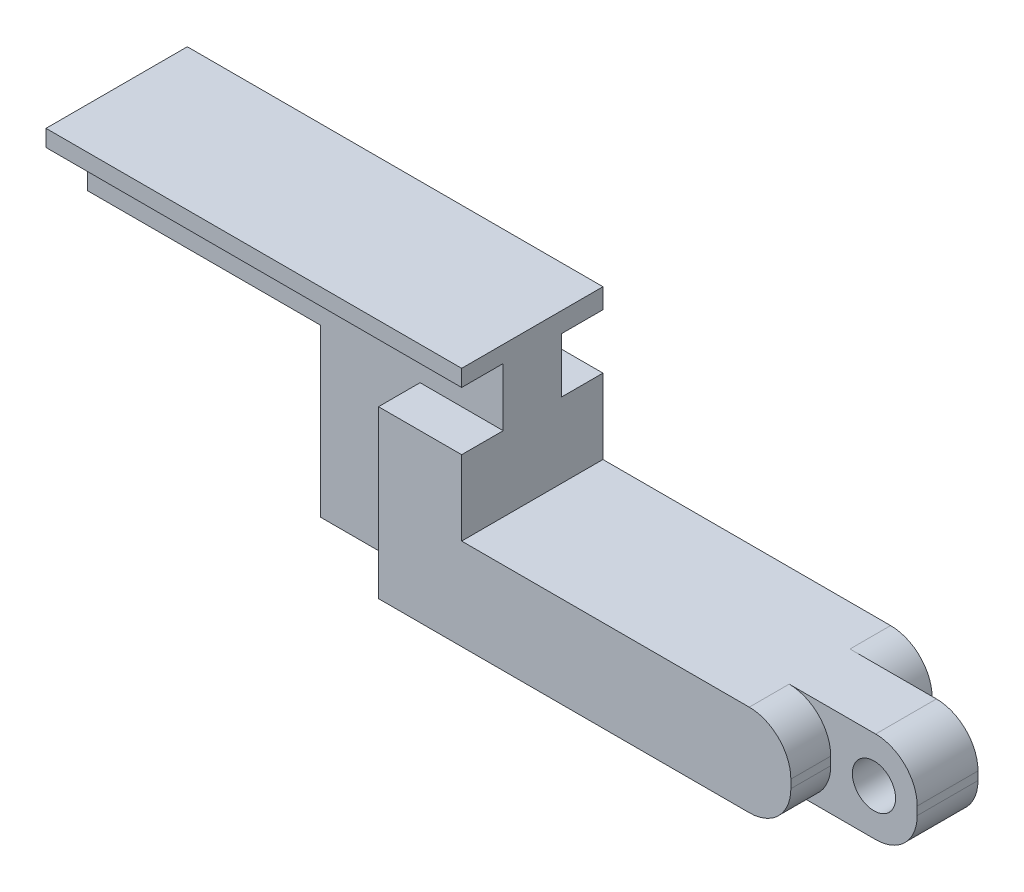
SolidWorks part; units mm, degrees
ref_plane "Front Plane" through (0, 0, 0) normal (0, 0, 1) x (1, 0, 0)
ref_plane "Top Plane" through (0, 0, 0) normal (0, 1, 0) x (1, 0, 0)
ref_plane "Right Plane" through (0, 0, 0) normal (1, 0, 0) x (0, 0, -1)
sketch "Sketch1" plane through (0, 0, 0) normal (1, 0, 0) x (0, 0, -1)
  line L0 (0, 0) -> (0, -36.83)
  line L1 (0, -36.83) -> (21.59, -36.83)
  line L2 (21.59, -36.83) -> (21.59, 0)
  line L3 (21.59, 0) -> (0, 0)
  dimension "D1" = 21.59
  dimension "D2" = 36.83
extrude "Boss-Extrude1" add sketch "Sketch1" along normal blind 127
sketch "Sketch2" plane through (0, 0, 0) normal (0, 0, 1) x (1, 0, 0)
  line L0 (0, -36.83) -> (0, -11.43)
  line L1 (0, 0) -> (0, -36.83) construction
  line L2 (0, -11.43) -> (50.8, -11.43)
  line L3 (50.8, -11.43) -> (50.8, -36.83)
  line L4 (127, -36.83) -> (0, -36.83) construction
  line L5 (50.8, -36.83) -> (0, -36.83)
  dimension "D1" = 50.8
  dimension "D2" = 25.4
extrude "Cut-Extrude1" cut sketch "Sketch2" against normal blind 25.4
sketch "Sketch3" plane through (0, 0, 0) normal (0, 0, 1) x (1, 0, 0)
  line L0 (127, 0) -> (63.5, 0)
  line L1 (127, 0) -> (0, 0) construction
  line L2 (63.5, 0) -> (63.5, -22.86)
  line L3 (63.5, -22.86) -> (127, -22.86)
  line L4 (127, 0) -> (127, -36.83) construction
  line L5 (127, -22.86) -> (127, 0)
  dimension "D1" = 63.5
  dimension "D2" = 22.86
extrude "Cut-Extrude2" cut sketch "Sketch3" against normal blind 22.86
sketch "Sketch4" plane through (0, 0, 0) normal (-1, 0, 0) x (0, 0, 1)
  line L0 (-21.59, -11.43) -> (-15.24, -11.43)
  line L1 (-21.59, -11.43) -> (0, -11.43) construction
  line L2 (-15.24, -11.43) -> (-15.24, -3.048)
  line L3 (-15.24, -3.048) -> (-21.59, -3.048)
  line L4 (-21.59, -11.43) -> (-21.59, 0) construction
  line L5 (-21.59, -3.048) -> (-21.59, -11.43)
  dimension "D1" = 8.382
  dimension "D2" = 6.35
extrude "Cut-Extrude3" cut sketch "Sketch4" against normal blind 69.85
sketch "Sketch5" plane through (0, 0, 0) normal (-1, 0, 0) x (0, 0, 1)
  line L0 (0, -11.43) -> (-6.35, -11.43)
  line L1 (-15.24, -11.43) -> (0, -11.43) construction
  line L2 (-6.35, -11.43) -> (-6.35, -2.54)
  line L3 (-6.35, -2.54) -> (0, -2.54)
  line L4 (0, 0) -> (0, -11.43) construction
  line L5 (0, -2.54) -> (0, -11.43)
  dimension "D1" = 8.89
  dimension "D2" = 6.35
extrude "Cut-Extrude4" cut sketch "Sketch5" against normal blind 69.85
sketch "Sketch6" plane through (127, 0, 0) normal (1, 0, 0) x (0, 0, -1)
  line L0 (0, -36.83) -> (0, -22.86)
  line L1 (0, -22.86) -> (6.096, -22.86)
  line L2 (0, -22.86) -> (21.59, -22.86) construction
  line L3 (6.096, -22.86) -> (6.096, -36.83)
  line L4 (0, -36.83) -> (21.59, -36.83) construction
  line L5 (6.096, -36.83) -> (0, -36.83)
  dimension "D1" = 6.096
extrude "Cut-Extrude5" cut sketch "Sketch6" against normal blind 13.208
sketch "Sketch7" plane through (127, 0, 0) normal (1, 0, 0) x (0, 0, -1)
  line L0 (21.59, -36.83) -> (21.59, -22.86)
  line L1 (21.59, -22.86) -> (15.3846, -22.86)
  line L2 (6.096, -22.86) -> (21.59, -22.86) construction
  line L3 (15.3846, -22.86) -> (15.3846, -36.83)
  line L4 (6.096, -36.83) -> (21.59, -36.83) construction
  line L5 (15.3846, -36.83) -> (21.59, -36.83)
extrude "Cut-Extrude6" cut sketch "Sketch7" against normal blind 13.208
sketch "Sketch8" plane through (0, 0, -6.096) normal (0, 0, 1) x (1, 0, 0)
  circle A0 centre (120.396, -29.845) radius 3.302
  dimension "D1" = 6.604
extrude "Cut-Extrude7" cut sketch "Sketch8" against normal blind 13.208
fillet "Fillet1" radius 6.35 1 edges at (113.792, -22.86, -3.048)
fillet "Fillet2" radius 6.35 1 edges at (113.792, -36.83, -3.048)
fillet "Fillet3" radius 6.35 1 edges at (113.792, -22.86, -18.4873)
fillet "Fillet4" radius 6.35 1 edges at (113.792, -36.83, -18.4873)
fillet "Fillet5" radius 6.35 1 edges at (127, -22.86, -10.7403)
fillet "Fillet6" radius 6.35 1 edges at (127, -36.83, -10.7403)
sketch "Sketch9" plane through (0, -11.43, 0) normal (0, -1, 0) x (1, 0, 0)
  line L0 (50.8, -15.24) -> (50.8, -6.35)
  line L1 (50.8, -6.35) -> (35.56, -6.35)
  line L2 (50.8, -6.35) -> (0, -6.35) construction
  line L3 (35.56, -6.35) -> (35.56, -15.24)
  line L4 (50.8, -15.24) -> (0, -15.24) construction
  line L5 (35.56, -15.24) -> (50.8, -15.24)
  dimension "D1" = 15.24
extrude "Boss-Extrude2" add sketch "Sketch9" along normal blind 25.4
